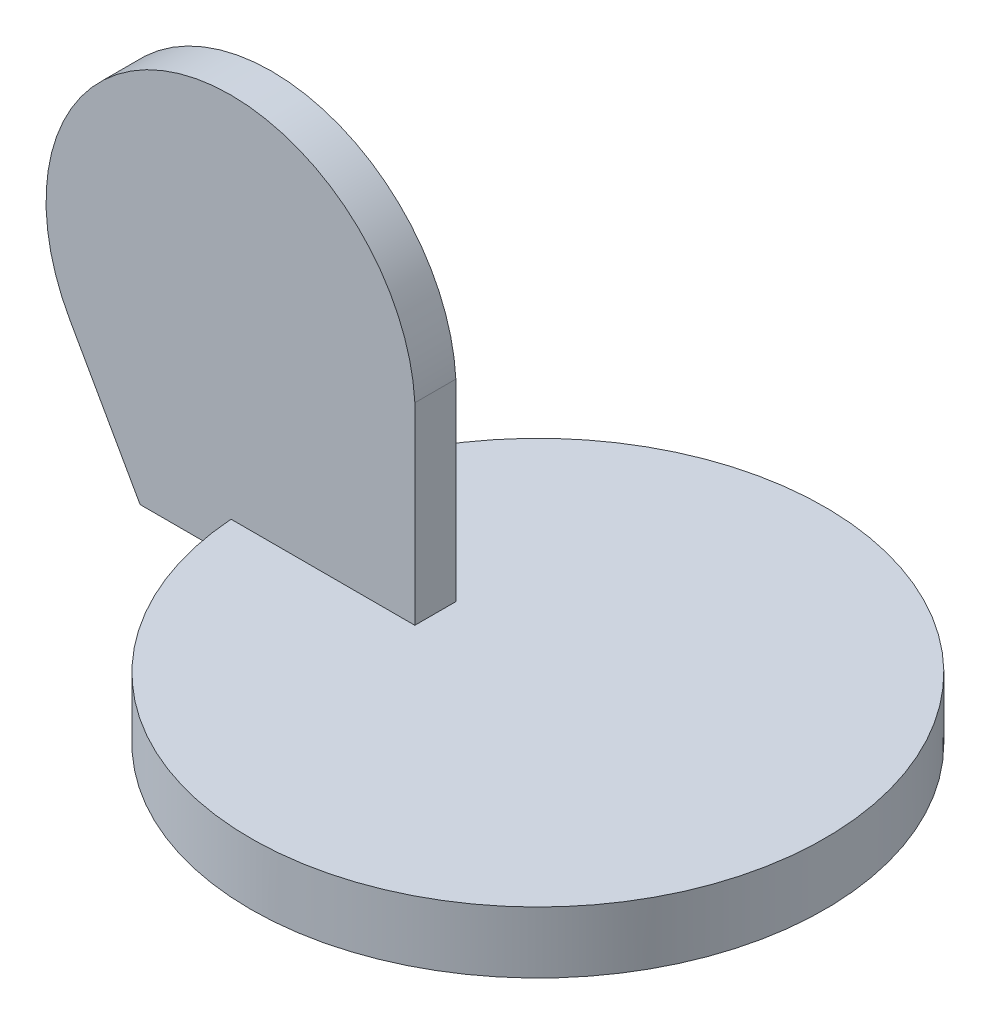
SolidWorks part; units mm, degrees
ref_plane "Front Plane" through (0, 0, 0) normal (0, 0, 1) x (1, 0, 0)
ref_plane "Top Plane" through (0, 0, 0) normal (0, 1, 0) x (1, 0, 0)
ref_plane "Right Plane" through (0, 0, 0) normal (1, 0, 0) x (0, 0, -1)
sketch "Sketch1" plane through (0, 0, 0) normal (0, 1, 0) x (1, 0, 0)
  circle A0 centre (0, 0) radius 70
  dimension "D1" = 140
extrude "Boss-Extrude2" add sketch "Sketch1" along normal blind 15 contours A0
sketch "Sketch2" plane through (0, 0, 0) normal (0, -1, 0) x (1, 0, 0)
  circle A0 centre (0, 0) radius 65
  dimension "D1" = 130
extrude "Boss-Extrude3" add sketch "Sketch2" along normal blind 3
sketch "Sketch3" plane through (0, 0, 0) normal (0, 0, 1) x (1, 0, 0)
  line L0 (-25, 62) -> (-25, 7)
  line L1 (-25, 7) -> (-92, 7)
  line L2 (-92, 7) -> (-109.1567, 37.5065)
  arc A0 (-109.1567, 37.5065) -> (-25, 62) centre (-69.9341, 59.5652) cw
  dimension "D5" = 45
  dimension "D1" = 25
  dimension "D2" = 7
  dimension "D3" = 55
  dimension "D4" = 67
  dimension "D6" = 35
extrude "Boss-Extrude4" add sketch "Sketch3" along normal mid plane 10 contours A0 L0 L1 L2
